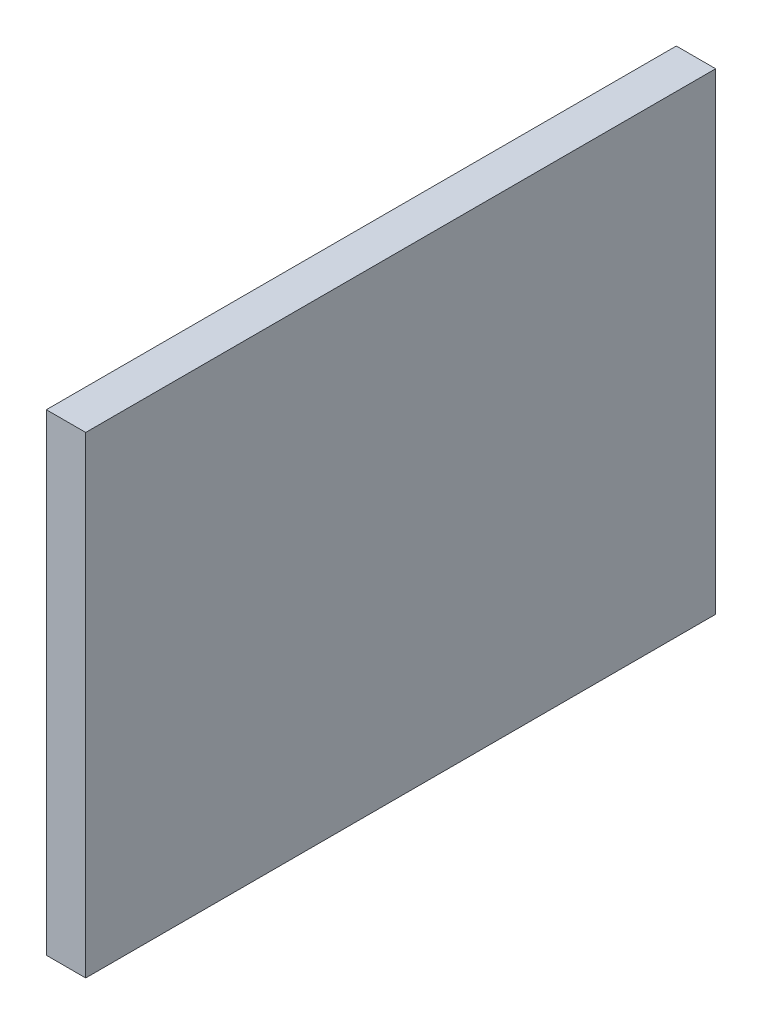
SolidWorks part; units mm, degrees
ref_plane "Front Plane" through (0, 0, 0) normal (0, 0, 1) x (1, 0, 0)
ref_plane "Top Plane" through (0, 0, 0) normal (0, 1, 0) x (1, 0, 0)
ref_plane "Right Plane" through (0, 0, 0) normal (1, 0, 0) x (0, 0, -1)
sketch "Sketch1" plane through (19, 0, 0) normal (1, 0, 0) x (0, 0, -1)
  line L0 (10, -9.798) -> (10, -11.1803)
  line L1 (10, -9.798) -> (10, -11.1803) construction
  line L2 (7.3, -13.1038) -> (7.3, -16)
  line L3 (7.3, -13.1038) -> (7.3, -16) construction
  line L4 (6.3, -17) -> (-6.3, -17)
  line L5 (6.3, -17) -> (-6.3, -17) construction
  line L6 (-7.3, -16) -> (-7.3, -13.1038)
  line L7 (-7.3, -16) -> (-7.3, -13.1038) construction
  line L8 (-10, -11.1803) -> (-10, -9.798)
  line L9 (-10, -11.1803) -> (-10, -9.798) construction
  line L10 (-13.5554, -3.5) -> (-17.5, -3.5)
  line L11 (-13.5554, -3.5) -> (-17.5, -3.5) construction
  line L12 (-17.5, 3.5) -> (-13.5554, 3.5)
  line L13 (-17.5, 3.5) -> (-13.5554, 3.5) construction
  line L14 (13.5554, 3.5) -> (17.5, 3.5)
  line L15 (13.5554, 3.5) -> (17.5, 3.5) construction
  line L16 (17.5, -3.5) -> (13.5554, -3.5)
  line L17 (17.5, -3.5) -> (13.5554, -3.5) construction
  line L18 (10.1, -9.8387) -> (10.1, -11.225)
  line L19 (7.4, -13.1624) -> (7.4, -16)
  line L20 (6.3, -17.1) -> (-6.3, -17.1)
  line L21 (-7.4, -16) -> (-7.4, -13.1624)
  line L22 (-10.1, -11.225) -> (-10.1, -9.8387)
  line L27 (-17.5, 6.6) -> (-15.775, 6.6)
  line L28 (-15.775, -6.6) -> (-17.5, -6.6)
  line L29 (-13.1, -12.49) -> (-13.1, -10.9909)
  line L30 (-10.4, -16) -> (-10.4, -14.8138)
  line L31 (6.3, -20.1) -> (-6.3, -20.1)
  line L32 (10.4, -14.8138) -> (10.4, -16)
  line L33 (13.1, -10.9909) -> (13.1, -12.49)
  line L34 (17.5, -6.6) -> (15.775, -6.6)
  line L35 (15.775, 6.6) -> (17.5, 6.6)
  line L45 (-17.5, 3.6) -> (-13.6327, 3.6) construction
  line L46 (-13.6327, -3.6) -> (-17.5, -3.6) construction
  line L47 (13.6327, 3.6) -> (17.5, 3.6) construction
  line L48 (17.5, -3.6) -> (13.6327, -3.6) construction
  arc A0 (7.3, -13.1038) -> (10, -11.1803) centre (0, 0) ccw
  arc A1 (7.3, -13.1038) -> (10, -11.1803) centre (0, 0) ccw construction
  arc A2 (6.3, -17) -> (7.3, -16) centre (6.3, -16) ccw
  arc A3 (6.3, -17) -> (7.3, -16) centre (6.3, -16) ccw construction
  arc A4 (-7.3, -16) -> (-6.3, -17) centre (-6.3, -16) ccw
  arc A5 (-7.3, -16) -> (-6.3, -17) centre (-6.3, -16) ccw construction
  arc A6 (-10, -11.1803) -> (-7.3, -13.1038) centre (0, 0) ccw
  arc A7 (-10, -11.1803) -> (-7.3, -13.1038) centre (0, 0) ccw construction
  arc A8 (-13.5554, -3.5) -> (-10, -9.798) centre (0, 0) ccw
  arc A9 (-13.5554, -3.5) -> (-10, -9.798) centre (0, 0) ccw construction
  arc A10 (-17.5, 3.5) -> (-17.5, -3.5) centre (-17.5, 0) ccw
  arc A11 (-17.5, 3.5) -> (-17.5, -3.5) centre (-17.5, 0) ccw construction
  arc A12 (13.5554, 3.5) -> (-13.5554, 3.5) centre (0, 0) ccw
  arc A13 (13.5554, 3.5) -> (-13.5554, 3.5) centre (0, 0) ccw construction
  arc A14 (17.5, -3.5) -> (17.5, 3.5) centre (17.5, 0) ccw
  arc A15 (17.5, -3.5) -> (17.5, 3.5) centre (17.5, 0) ccw construction
  arc A16 (10, -9.798) -> (13.5554, -3.5) centre (0, 0) ccw
  arc A17 (10, -9.798) -> (13.5554, -3.5) centre (0, 0) ccw construction
  arc A18 (7.4, -13.1624) -> (10.1, -11.225) centre (0, 0) ccw
  arc A19 (6.3, -17.1) -> (7.4, -16) centre (6.3, -16) ccw
  arc A20 (-7.4, -16) -> (-6.3, -17.1) centre (-6.3, -16) ccw
  arc A21 (-10.1, -11.225) -> (-7.4, -13.1624) centre (0, 0) ccw
  arc A22 (-13.6327, -3.6) -> (-10.1, -9.8387) centre (0, 0) ccw
  arc A24 (13.6327, 3.6) -> (-13.6327, 3.6) centre (0, 0) ccw
  arc A26 (10.1, -9.8387) -> (13.6327, -3.6) centre (0, 0) ccw
  arc A27 (15.775, 6.6) -> (-15.775, 6.6) centre (0, 0) ccw
  arc A28 (-17.5, 6.6) -> (-17.5, -6.6) centre (-17.5, 0) ccw
  arc A29 (-15.775, -6.6) -> (-13.1, -10.9909) centre (0, 0) ccw
  arc A30 (-13.1, -12.49) -> (-10.4, -14.8138) centre (0, 0) ccw
  arc A31 (-10.4, -16) -> (-6.3, -20.1) centre (-6.3, -16) ccw
  arc A32 (6.3, -20.1) -> (10.4, -16) centre (6.3, -16) ccw
  arc A33 (10.4, -14.8138) -> (13.1, -12.49) centre (0, 0) ccw
  arc A34 (13.1, -10.9909) -> (15.775, -6.6) centre (0, 0) ccw
  arc A35 (17.5, -6.6) -> (17.5, 6.6) centre (17.5, 0) ccw
  arc A36 (13.6327, 3.6) -> (13.6327, -3.6) centre (0, 0) cw
  arc A37 (-13.6327, 3.6) -> (-13.6327, -3.6) centre (0, 0) ccw
  arc A45 (-17.5, 3.6) -> (-17.5, -3.6) centre (-17.5, 0) ccw construction
  arc A46 (17.5, -3.6) -> (17.5, 3.6) centre (17.5, 0) ccw construction
  dimension "D1" = 0.1
  dimension "D2" = 3
extrude "Boss-Extrude1" add sketch "Sketch1" against normal blind 12
sketch "Sketch2" plane through (7, 0, 0) normal (-1, 0, 0) x (0, 0, 1)
  line L0 (17.5, 3.5) -> (13.5554, 3.5) construction
  line L1 (13.5554, -3.5) -> (17.5, -3.5) construction
  line L2 (-13.5554, 3.5) -> (-17.5, 3.5) construction
  line L3 (-17.5, -3.5) -> (-13.5554, -3.5) construction
  line L4 (17.5, 3.5) -> (13.6587, 3.5)
  line L5 (13.6587, -3.5) -> (17.5, -3.5)
  line L6 (-13.6587, 3.5) -> (-17.5, 3.5)
  line L7 (-17.5, -3.5) -> (-13.6587, -3.5)
  circle A0 centre (17.5, 0) radius 2.25 construction
  arc A1 (17.5, -3.5) -> (17.5, 3.5) centre (17.5, 0) ccw construction
  circle A2 centre (-17.5, 0) radius 2.25 construction
  arc A3 (-17.5, 3.5) -> (-17.5, -3.5) centre (-17.5, 0) ccw construction
  arc A4 (10.1, -9.8387) -> (-10.1, -9.8387) centre (0, 0) ccw construction
  circle A5 centre (17.5, 0) radius 2.25 construction
  arc A6 (17.5, -3.5) -> (17.5, 3.5) centre (17.5, 0) ccw
  circle A7 centre (-17.5, 0) radius 2.25 construction
  arc A8 (-17.5, 3.5) -> (-17.5, -3.5) centre (-17.5, 0) ccw
  arc A9 (13.6587, -3.5) -> (13.6587, 3.5) centre (0, 0) ccw
  arc A10 (-13.6587, 3.5) -> (-13.6587, -3.5) centre (0, 0) ccw
  circle A11 centre (-17.5, 0) radius 0.5
  circle A12 centre (17.5, 0) radius 0.5
  dimension "D1" = 1
extrude "Boss-Extrude2" add sketch "Sketch2" along normal blind 6
sketch "Sketch3" plane through (19, 0, 0) normal (1, 0, 0) x (0, 0, -1)
  line L1 (-40, 30) -> (40, 30)
  line L2 (-40, 30) -> (-40, -30)
  line L3 (-40, -30) -> (40, -30)
  line L4 (40, 30) -> (40, -30)
  line L5 (-40, 30) -> (40, -30) construction
  line L6 (-40, -30) -> (40, 30) construction
  point P0 (0, 0)
  dimension "D1" = 80
  dimension "D2" = 60
extrude "Boss-Extrude3" add sketch "Sketch3" along normal blind 5
